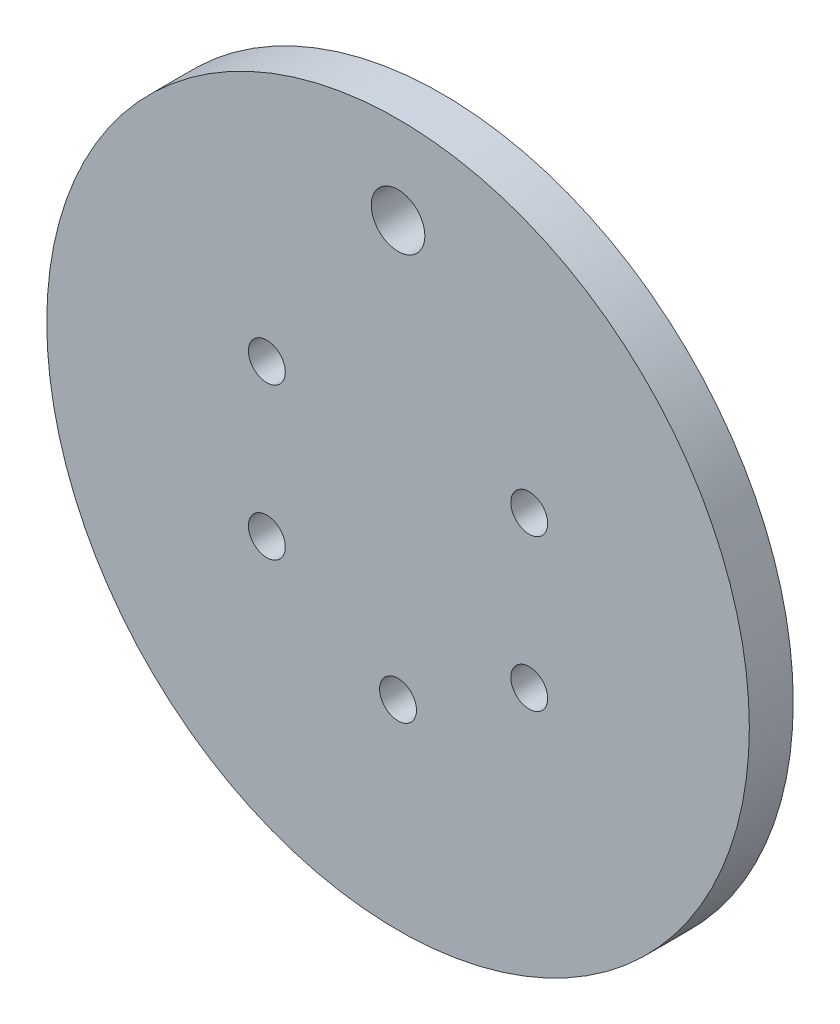
SolidWorks part; units mm, degrees
ref_plane "前视基准面" through (0, 0, 0) normal (0, 0, 1) x (1, 0, 0)
ref_plane "上视基准面" through (0, 0, 0) normal (0, 1, 0) x (1, 0, 0)
ref_plane "右视基准面" through (0, 0, 0) normal (1, 0, 0) x (0, 0, -1)
other "Configuration Table"
sketch "草图1" plane through (0, 0, 0) normal (0, 0, 1) x (1, 0, 0)
  line L0 (0, 0) -> (0, 40) construction
  circle A0 centre (0, 0) radius 40
  circle A1 centre (0, 17.25) radius 2.1
  circle A2 centre (14.9389, 8.625) radius 2.1
  circle A3 centre (14.9389, -8.625) radius 2.1
  circle A4 centre (0, -17.25) radius 2.1
  circle A5 centre (-14.9389, -8.625) radius 2.1
  circle A6 centre (-14.9389, 8.625) radius 2.1
  point P19 (0, 0)
  dimension "D1" = 80
  dimension "D3" = 4.2
  dimension "D2" = 17.25
  dimension "D4" = 6
extrude "凸台-拉伸1" add sketch "草图1" along normal blind 5 contours A6 | A0 | A2 | A3 | A4 | A5
sketch "草图2" plane through (0, 0, 5) normal (0, 0, 1) x (1, 0, 0)
  circle A0 centre (0, 30) radius 3.05
  dimension "D1" = 6.1
  dimension "D2" = 30
extrude "切除-拉伸2" cut sketch "草图2" against normal blind 10
